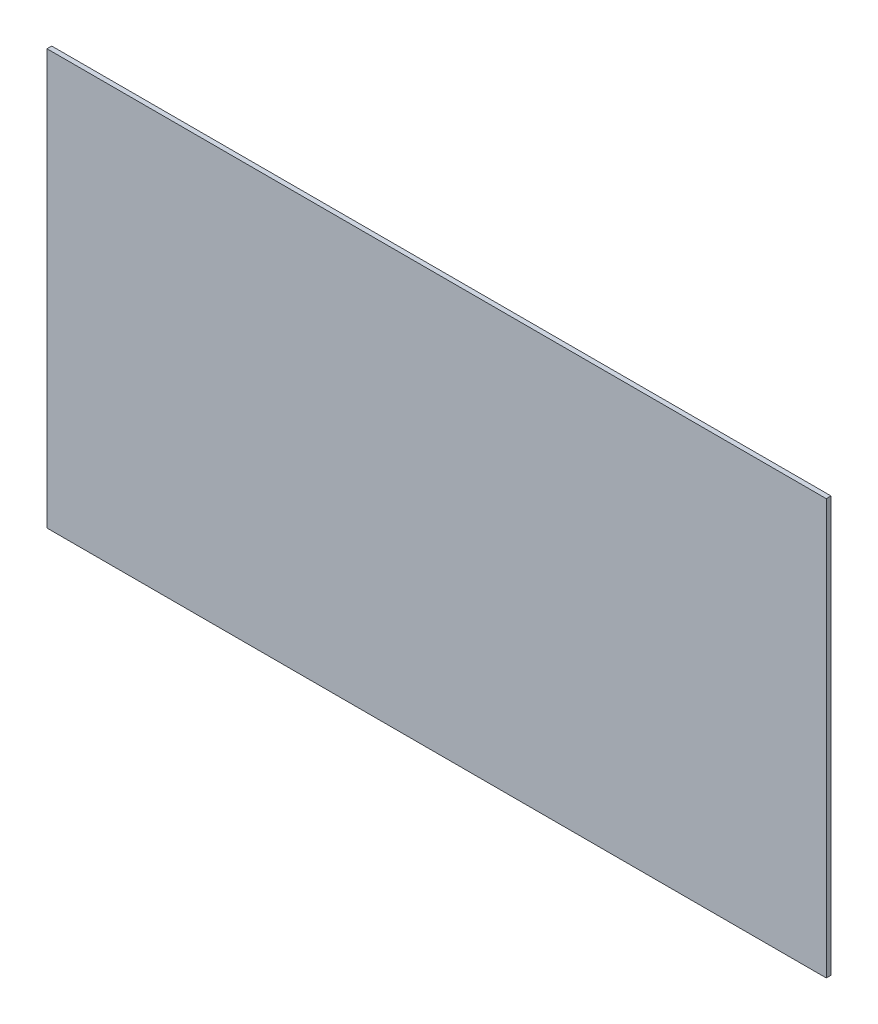
SolidWorks part; units mm, degrees
ref_plane "Front Plane" through (0, 0, 0) normal (0, 0, 1) x (1, 0, 0)
ref_plane "Top Plane" through (0, 0, 0) normal (0, 1, 0) x (1, 0, 0)
ref_plane "Right Plane" through (0, 0, 0) normal (1, 0, 0) x (0, 0, -1)
sketch "Sketch1" plane through (0, 0, 0) normal (0, 0, 1) x (1, 0, 0)
  line L1 (0, 0) -> (524.51, 0)
  line L2 (0, 0) -> (0, 279.4)
  line L3 (0, 279.4) -> (524.51, 279.4)
  line L4 (524.51, 0) -> (524.51, 279.4)
  dimension "D1" = 524.51
  dimension "D2" = 279.4
extrude "Boss-Extrude2" add sketch "Sketch1" along normal blind 3.1852
